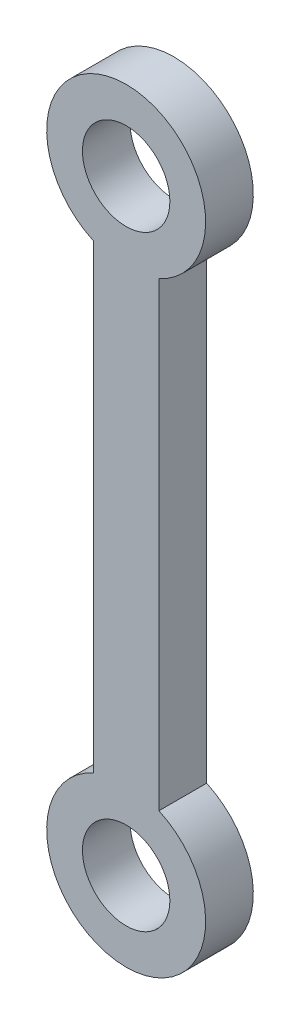
SolidWorks part; units mm, degrees
ref_plane "Front Plane" through (0, 0, 0) normal (0, 0, 1) x (1, 0, 0)
ref_plane "Top Plane" through (0, 0, 0) normal (0, 1, 0) x (1, 0, 0)
ref_plane "Right Plane" through (0, 0, 0) normal (1, 0, 0) x (0, 0, -1)
sketch "Sketch3" plane through (0, 0, 0) normal (0, 0, 1) x (1, 0, 0)
  line L3 (644.7499, -1262.5916) -> (644.7499, -1291.5818)
  line L5 (640.6253, -1262.5916) -> (640.6253, -1291.5818)
  arc A0 (644.7499, -1262.5916) -> (640.6253, -1262.5916) centre (642.6876, -1258.0367) ccw
  arc A1 (640.6253, -1291.5818) -> (644.7499, -1291.5818) centre (642.6876, -1296.1367) ccw
  circle A2 centre (642.6876, -1296.1367) radius 2.75
  circle A3 centre (642.6876, -1258.0367) radius 2.75
  dimension "D1" = 5.5
  dimension "D2" = 5
  dimension "D3" = 28.9902
  dimension "D5" = 5
  dimension "D4" = 5.5
extrude "Boss-Extrude3" add sketch "Sketch3" along normal mid plane 3 separate body
